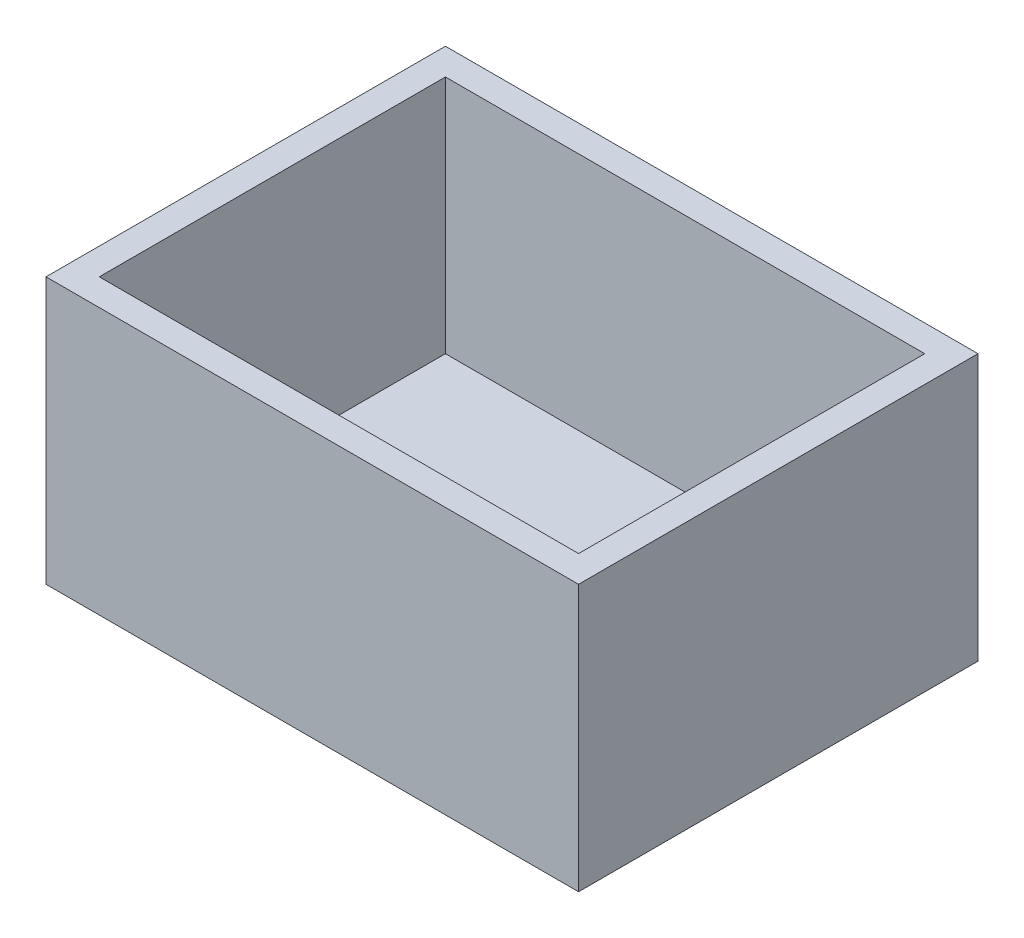
SolidWorks part; units mm, degrees
ref_plane "Front Plane" through (0, 0, 0) normal (0, 0, 1) x (1, 0, 0)
ref_plane "Top Plane" through (0, 0, 0) normal (0, 1, 0) x (1, 0, 0)
ref_plane "Right Plane" through (0, 0, 0) normal (1, 0, 0) x (0, 0, -1)
sketch "Sketch1" plane through (0, 0, 0) normal (0, 1, 0) x (1, 0, 0)
  line L0 (-20, -15) -> (20, -15)
  line L1 (20, -15) -> (20, 15)
  line L2 (20, 15) -> (-20, 15)
  line L3 (-20, 15) -> (-20, -15)
extrude "Boss-Extrude1" add sketch "Sketch1" along normal blind 20
shell "Shell1" thickness 2
